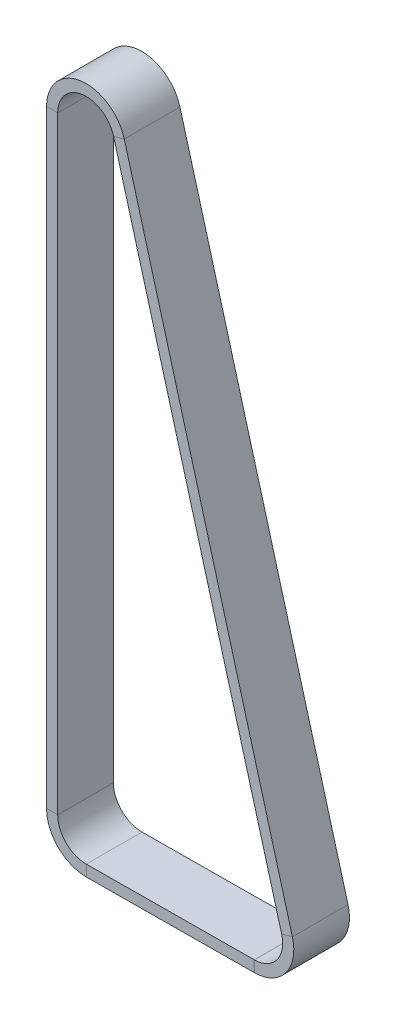
SolidWorks part; units mm, degrees
ref_plane "Front Plane" through (0, 0, 0) normal (0, 0, 1) x (1, 0, 0)
ref_plane "Top Plane" through (0, 0, 0) normal (0, 1, 0) x (1, 0, 0)
ref_plane "Right Plane" through (0, 0, 0) normal (1, 0, 0) x (0, 0, -1)
sketch "Sketch2" plane through (0, 0, 0) normal (0, 0, 1) x (1, 0, 0)
  line L0 (0, 0) -> (1, 0) construction
  line L1 (0, 0) -> (0, 1) construction
  line L2 (0.0414, -6.1121) -> (-30.1633, -6.3168)
  line L3 (-36.317, -0.2048) -> (-36.317, 109.0345)
  line L4 (-24.3144, 110.6662) -> (5.8904, 1.6318)
  arc A0 (5.8904, 1.6318) -> (0.0414, -6.1121) centre (0, 0) cw
  arc A1 (-30.1633, -6.3168) -> (-36.317, -0.2048) centre (-30.2048, -0.2048) cw
  arc A2 (-36.317, 109.0345) -> (-24.3144, 110.6662) centre (-30.2048, 109.0345) cw
sketch "Sketch3" plane through (0, 0, 0) normal (1, 0, 0) x (0, 0, -1)
  line L2 (0, 1.6318) -> (0, -6.1121) construction
  line L3 (0, 1.6318) -> (0, -6.1121)
  line L5 (-5, -7.1121) -> (5, -7.1121)
  line L6 (-5, -7.1121) -> (-5, -5.1121)
  line L7 (-5, -5.1121) -> (5, -5.1121)
  line L8 (5, -7.1121) -> (5, -5.1121)
  line L9 (-5, -7.1121) -> (5, -5.1121) construction
  line L10 (-5, -5.1121) -> (5, -7.1121) construction
  dimension "D1" = 10
  dimension "D2" = 2
sweep "Sweep1" add profiles "Sketch3" path "Sketch2"
